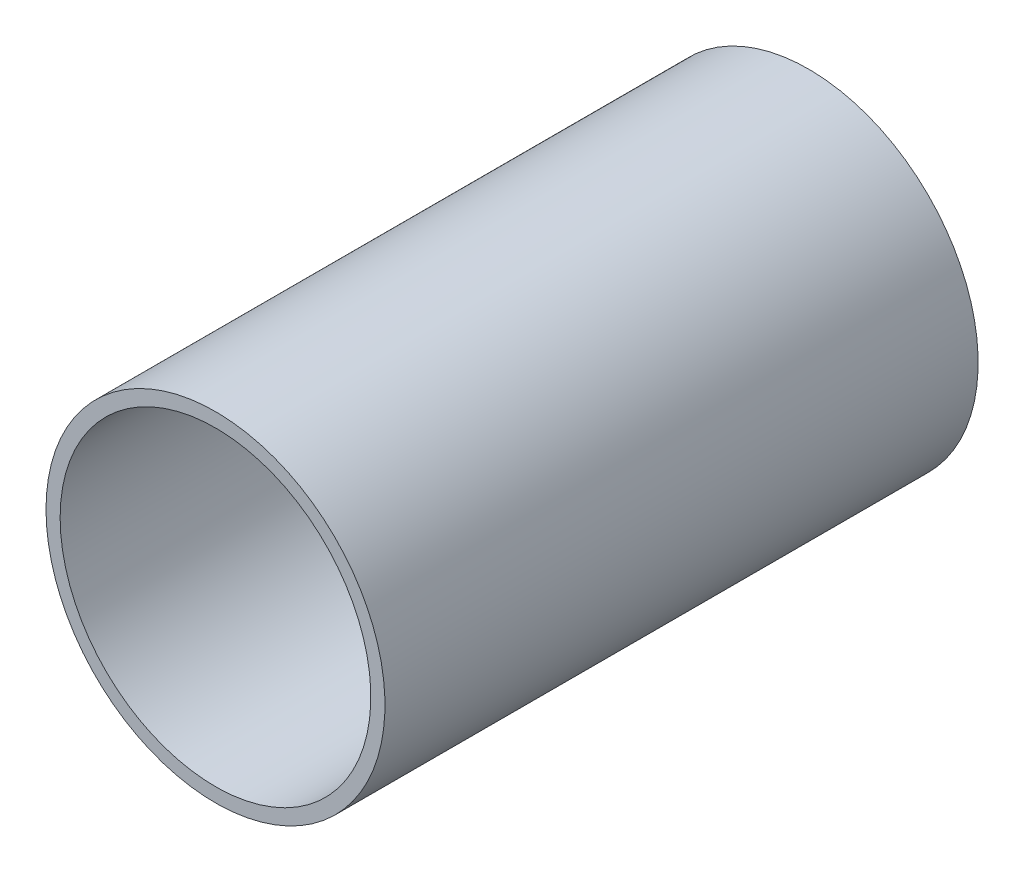
SolidWorks part; units mm, degrees
ref_plane "Front Plane" through (0, 0, 0) normal (0, 0, 1) x (1, 0, 0)
ref_plane "Top Plane" through (0, 0, 0) normal (0, 1, 0) x (1, 0, 0)
ref_plane "Right Plane" through (0, 0, 0) normal (1, 0, 0) x (0, 0, -1)
sketch "Sketch1" plane through (0, 0, 0) normal (0, 0, 1) x (1, 0, 0)
  circle A0 centre (0, 0) radius 12
  circle A1 centre (0, 0) radius 11
  dimension "D1" = 24
  dimension "D2" = 22
extrude "Boss-Extrude1" add sketch "Sketch1" along normal blind 42
